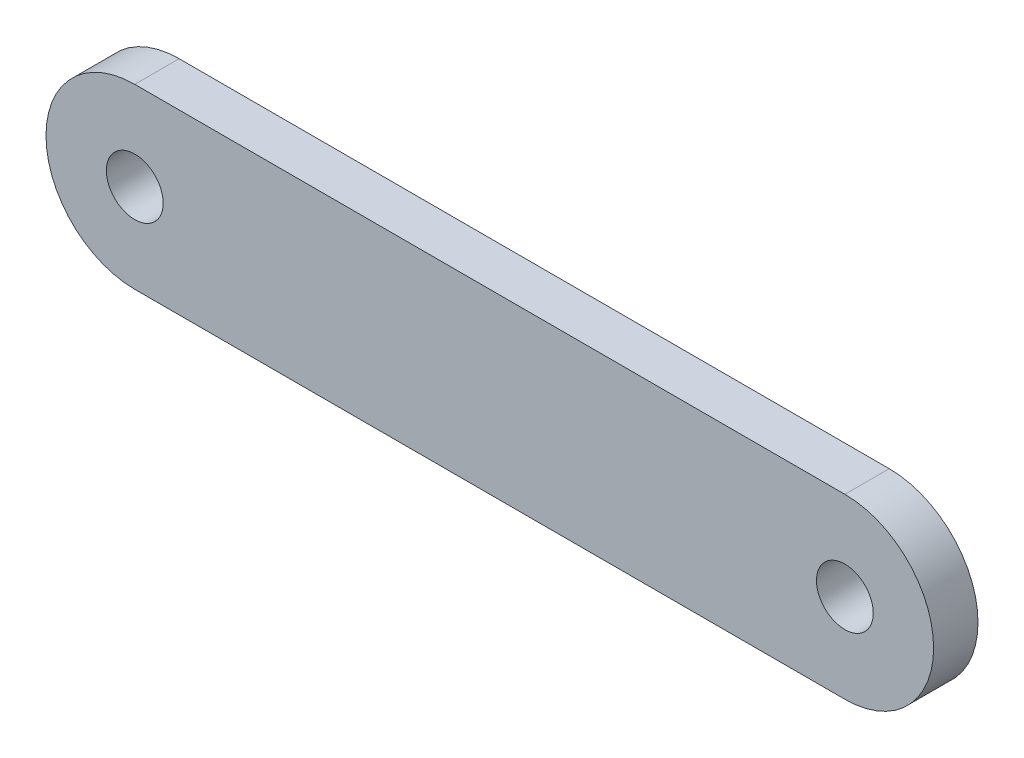
SolidWorks part; units mm, degrees
ref_plane "Front Plane" through (0, 0, 0) normal (0, 0, 1) x (1, 0, 0)
ref_plane "Top Plane" through (0, 0, 0) normal (0, 1, 0) x (1, 0, 0)
ref_plane "Right Plane" through (0, 0, 0) normal (1, 0, 0) x (0, 0, -1)
sketch "Sketch1" plane through (0, 0, 0) normal (0, 0, 1) x (1, 0, 0)
  line L0 (0, 0) -> (50.8, 0) construction
  line L1 (0, 6.35) -> (50.8, 6.35)
  line L2 (0, -6.35) -> (50.8, -6.35)
  arc A0 (0, 6.35) -> (0, -6.35) centre (0, 0) ccw
  arc A1 (50.8, -6.35) -> (50.8, 6.35) centre (50.8, 0) ccw
  circle A2 centre (0, 0) radius 2.032
  circle A3 centre (50.8, 0) radius 2.032
  point P3 (25.4, 0)
  dimension "D2" = 6.35
  dimension "D3" = 4.064
  dimension "D1" = 50.8
extrude "Boss-Extrude1" add sketch "Sketch1" along normal blind 3.175
